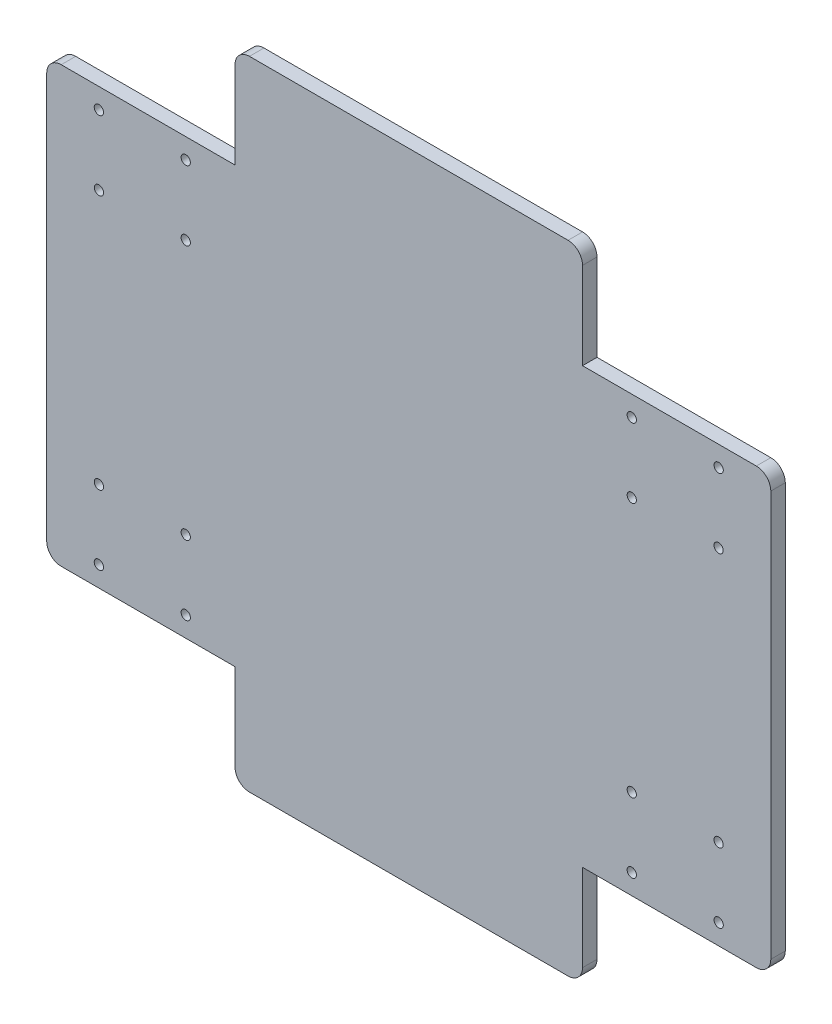
SolidWorks part; units mm, degrees
ref_plane "前视基准面" through (0, 0, 0) normal (0, 0, 1) x (1, 0, 0)
ref_plane "上视基准面" through (0, 0, 0) normal (0, 1, 0) x (1, 0, 0)
ref_plane "右视基准面" through (0, 0, 0) normal (1, 0, 0) x (0, 0, -1)
sketch "草图1" plane through (0, 0, 0) normal (0, 0, 1) x (1, 0, 0)
  line L0 (-67.0818, 36.6419) -> (-2.0818, 36.6419)
  line L1 (-2.0818, 36.6419) -> (-2.0818, 71.6419)
  line L2 (-2.0818, 71.6419) -> (117.9182, 71.6419)
  line L3 (117.9182, 71.6419) -> (117.9182, 36.6419)
  line L4 (117.9182, 36.6419) -> (182.9182, 36.6419)
  line L5 (182.9182, 36.6419) -> (182.9182, -113.3581)
  line L6 (182.9182, -113.3581) -> (117.9182, -113.3581)
  line L7 (117.9182, -113.3581) -> (117.9182, -148.3581)
  line L8 (117.9182, -148.3581) -> (-2.0818, -148.3581)
  line L9 (-2.0818, -148.3581) -> (-2.0818, -113.3581)
  line L10 (-2.0818, -113.3581) -> (-67.0818, -113.3581)
  line L11 (-67.0818, -113.3581) -> (-67.0818, 36.6419)
  line L12 (-34.5818, 36.6419) -> (-34.5818, -113.3581) construction
  line L19 (-67.0818, -38.3581) -> (182.9182, -38.3581) construction
  line L20 (150.4182, 36.6419) -> (150.4182, -113.3581) construction
  line L21 (57.9182, -148.3581) -> (57.9182, 71.6419) construction
  circle A0 centre (-49.0813, 29.6419) radius 1.6
  circle A1 centre (-19.0813, 29.6734) radius 1.6
  circle A2 centre (-49.0601, 5.6419) radius 1.6
  circle A3 centre (-19.0813, 5.6734) radius 1.6
  circle A4 centre (164.8965, 5.6419) radius 1.6
  circle A5 centre (134.9177, 5.6734) radius 1.6
  circle A6 centre (134.9177, 29.6734) radius 1.6
  circle A7 centre (164.9177, 29.6419) radius 1.6
  circle A8 centre (134.9177, -82.3896) radius 1.6
  circle A9 centre (164.8965, -82.3581) radius 1.6
  circle A10 centre (164.9177, -106.3581) radius 1.6
  circle A11 centre (134.9177, -106.3896) radius 1.6
  circle A12 centre (-49.0601, -82.3581) radius 1.6
  circle A13 centre (-19.0813, -82.3896) radius 1.6
  circle A14 centre (-19.0813, -106.3896) radius 1.6
  circle A15 centre (-49.0813, -106.3581) radius 1.6
  dimension "D1" = 7
  dimension "D11" = 3.2
  dimension "D12" = 3.2
  dimension "D13" = 3.2
  dimension "D14" = 3.2
  dimension "D15" = 3.2
  dimension "D16" = 24
  dimension "D2" = 24
  dimension "D3" = 30
  dimension "D4" = 65
  dimension "D5" = 120
  dimension "D6" = 65
  dimension "D7" = 35
  dimension "D8" = 35
  dimension "D9" = 150
  dimension "D10" = 35
extrude "凸台-拉伸1" add sketch "草图1" along normal blind 5
fillet "圆角1" radius 5 8 edges at (-2.0818, -148.3581, 2.5) (-67.0818, -113.3581, 2.5) (-67.0818, 36.6419, 2.5) (-2.0818, 71.6419, 2.5) (117.9182, -148.3581, 2.5) (182.9182, -113.3581, 2.5) (182.9182, 36.6419, 2.5) (117.9182, 71.6419, 2.5)
